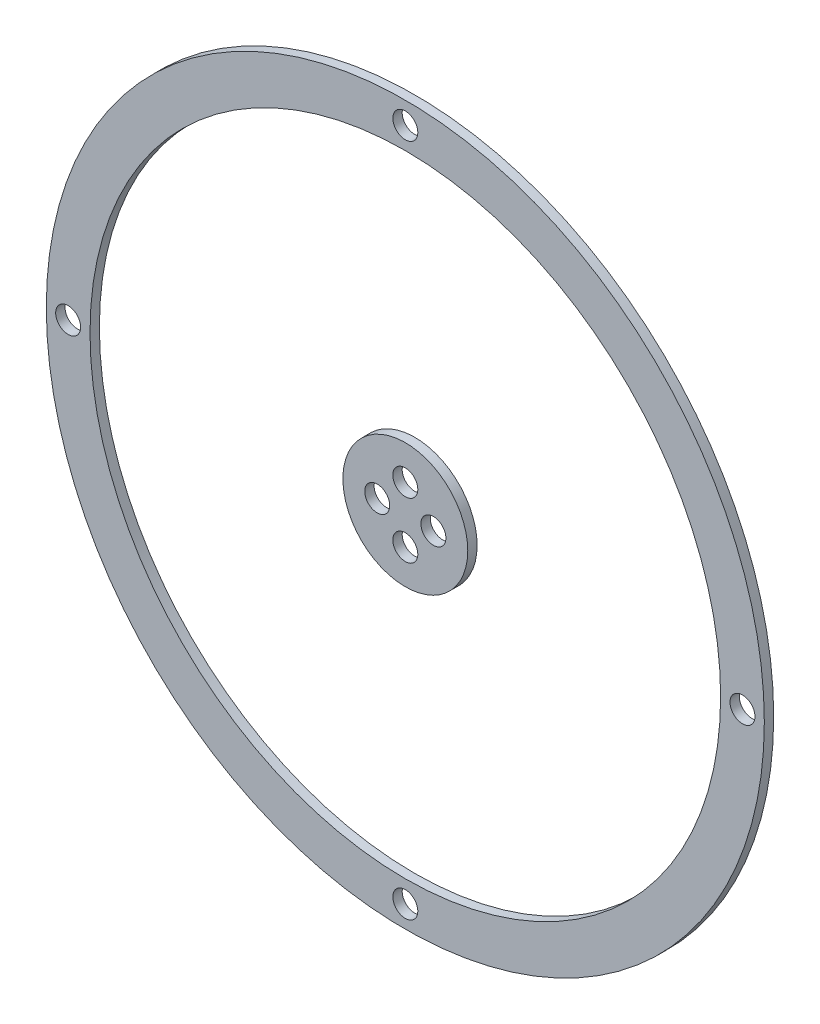
SolidWorks part; units mm, degrees
ref_plane "Alzado" through (0, 0, 0) normal (0, 0, 1) x (1, 0, 0)
ref_plane "Planta" through (0, 0, 0) normal (0, 1, 0) x (1, 0, 0)
ref_plane "Vista lateral" through (0, 0, 0) normal (1, 0, 0) x (0, 0, -1)
sketch "Croquis1" plane through (0, 0, 0) normal (0, 0, 1) x (1, 0, 0)
  circle A0 centre (0, 0) radius 57.5
  circle A1 centre (0, 0) radius 54 construction
  circle A2 centre (0, 54) radius 2
  circle A3 centre (0, 0) radius 50.5
  circle A4 centre (0, 0) radius 10
  circle A5 centre (0, 4.5) radius 2
  circle A6 centre (4.5, 0) radius 2
  circle A7 centre (54, 0) radius 2
  circle A8 centre (0, -4.5) radius 2
  circle A9 centre (0, -54) radius 2
  circle A10 centre (-4.5, 0) radius 2
  circle A11 centre (-54, 0) radius 2
  point P10 (0, 0)
  point P25 (0, 0)
  dimension "D1" = 115
  dimension "D2" = 108
  dimension "D3" = 4
  dimension "D4" = 7
  dimension "D5" = 20
  dimension "D6" = 4
  dimension "D7" = 4.5
  dimension "D8" = 4
extrude "Saliente-Extruir1" add sketch "Croquis1" along normal blind 1.5 contours A0 A11 A9 A7 A3 A2 | A4 A10 A8 A6 A5
